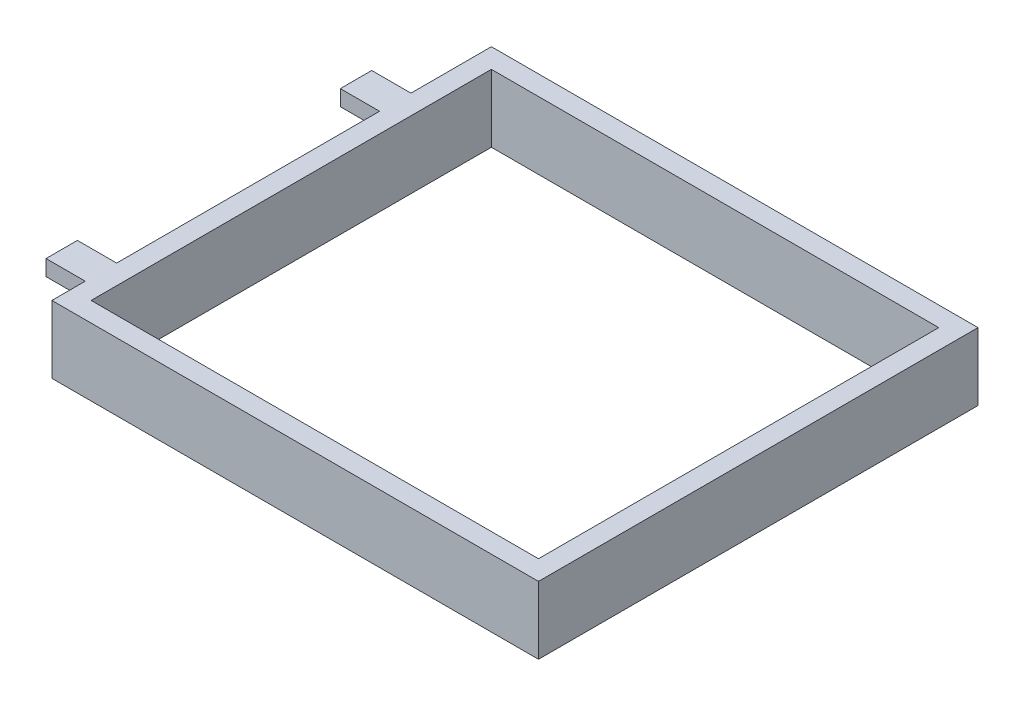
SolidWorks part; units mm, degrees
ref_plane "Front Plane" through (0, 0, 0) normal (0, 0, 1) x (1, 0, 0)
ref_plane "Top Plane" through (0, 0, 0) normal (0, 1, 0) x (1, 0, 0)
ref_plane "Right Plane" through (0, 0, 0) normal (1, 0, 0) x (0, 0, -1)
sketch "Sketch1" plane through (0, 0, 0) normal (0, 1, 0) x (1, 0, 0)
  line L1 (0, 0) -> (310, 0)
  line L2 (0, 0) -> (0, 280)
  line L3 (0, 280) -> (310, 280)
  line L4 (310, 0) -> (310, 280)
  line L5 (12.5, 267.5) -> (297.5, 267.5)
  line L6 (12.5, 267.5) -> (12.5, 12.5)
  line L7 (12.5, 12.5) -> (297.5, 12.5)
  line L8 (297.5, 267.5) -> (297.5, 12.5)
  dimension "D1" = 310
  dimension "D2" = 280
  dimension "D3" = 12.5
  dimension "D4" = 12.5
  dimension "D5" = 12.5
  dimension "D6" = 12.5
extrude "Boss-Extrude1" add sketch "Sketch1" along normal blind 43
sketch "Sketch2" plane through (0, 0, 0) normal (-1, 0, 0) x (0, 0, 1)
  line L0 (-280, 43) -> (0, 43) construction
  line L1 (-228.75, 43) -> (-208.75, 43)
  line L2 (-228.75, 43) -> (-228.75, 33)
  line L3 (-228.75, 33) -> (-208.75, 33)
  line L4 (-208.75, 43) -> (-208.75, 33)
  line L5 (-208.75, 43) -> (-41.25, 43) construction
  line L6 (-41.25, 43) -> (-21.25, 43)
  line L7 (-41.25, 43) -> (-41.25, 33)
  line L8 (-41.25, 33) -> (-21.25, 33)
  line L9 (-21.25, 43) -> (-21.25, 33)
  line L10 (-280, 43) -> (-280, 0) construction
  point P10 (-218.75, 33)
  point P11 (-31.25, 33)
  point P12 (-125, 43)
  dimension "D1" = 20
  dimension "D2" = 20
  dimension "D3" = 10
  dimension "D4" = 10
  dimension "D5" = 187.5
  dimension "D6" = 155
extrude "Boss-Extrude2" add sketch "Sketch2" along normal blind 25
sketch "Sketch3" plane through (0, 33, 0) normal (0, -1, 0) x (1, 0, 0)
  line L0 (-25, -208.75) -> (0, -208.75) construction
  line L1 (-25, -228.75) -> (-25, -208.75) construction
  line L2 (-25, -21.25) -> (0, -21.25) construction
  line L3 (-25, -41.25) -> (-25, -21.25) construction
  circle A0 centre (-15, -218.75) radius 5
  circle A1 centre (-15, -31.25) radius 5
  dimension "D1" = 10
  dimension "D4" = 10
  dimension "D2" = 10
  dimension "D3" = 10
  dimension "D5" = 10
  dimension "D6" = 10
